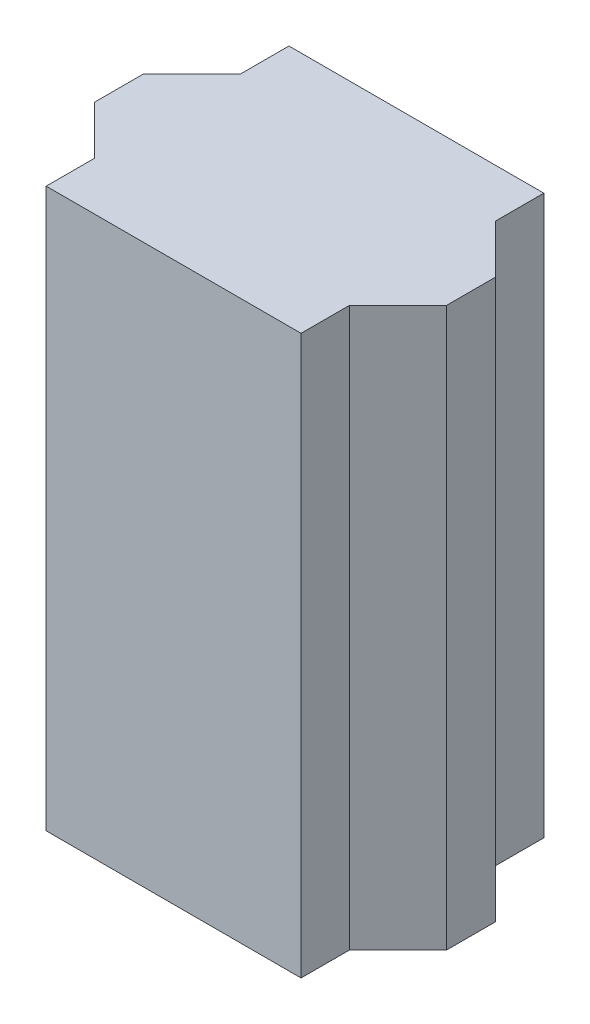
SolidWorks part; units mm, degrees
ref_plane "Спереди" through (0, 0, 0) normal (0, 0, 1) x (1, 0, 0)
ref_plane "Сверху" through (0, 0, 0) normal (0, 1, 0) x (1, 0, 0)
ref_plane "Справа" through (0, 0, 0) normal (1, 0, 0) x (0, 0, -1)
ref_plane "Плоскость4" through (0, 5, 0) normal (0, 1, 0) x (1, 0, 0)
sketch "Эскиз1" plane through (0, 5, 0) normal (0, 1, 0) x (1, 0, 0)
  line L1 (-5.25, -28) -> (-5.25, -26)
  line L2 (-5.75, -28) -> (-4.75, -28) construction
  line L3 (-5.25, -26) -> (-7.25, -24)
  line L4 (-5.25, -26) -> (-7.25, -24) construction
  line L5 (-7.25, -24) -> (-7.25, -22) construction
  line L6 (-7.25, -24) -> (-7.25, -22)
  line L7 (-7.25, -22) -> (-5.25, -20)
  line L8 (-4.25, -20.4142) -> (-5.25, -20) construction
  line L9 (-5.25, -20) -> (-5.25, -17.25) construction
  line L10 (-5.25, -20) -> (-5.25, -18)
  line L11 (-5.25, -18) -> (5.25, -18)
  line L12 (5.25, -17.25) -> (5.25, -20) construction
  line L13 (5.25, -18) -> (5.25, -20)
  line L14 (5.25, -20) -> (7.25, -22)
  line L15 (7.25, -22) -> (7.25, -24)
  line L16 (7.25, -22) -> (7.25, -24) construction
  line L17 (7.25, -24) -> (5.25, -26)
  line L18 (5.25, -26) -> (5.25, -28)
  line L19 (5.25, -26) -> (5.25, -33.5) construction
  line L20 (5.25, -28) -> (-5.25, -28)
extrude "Бобышка-Вытянуть1" add sketch "Эскиз1" along normal blind 23
